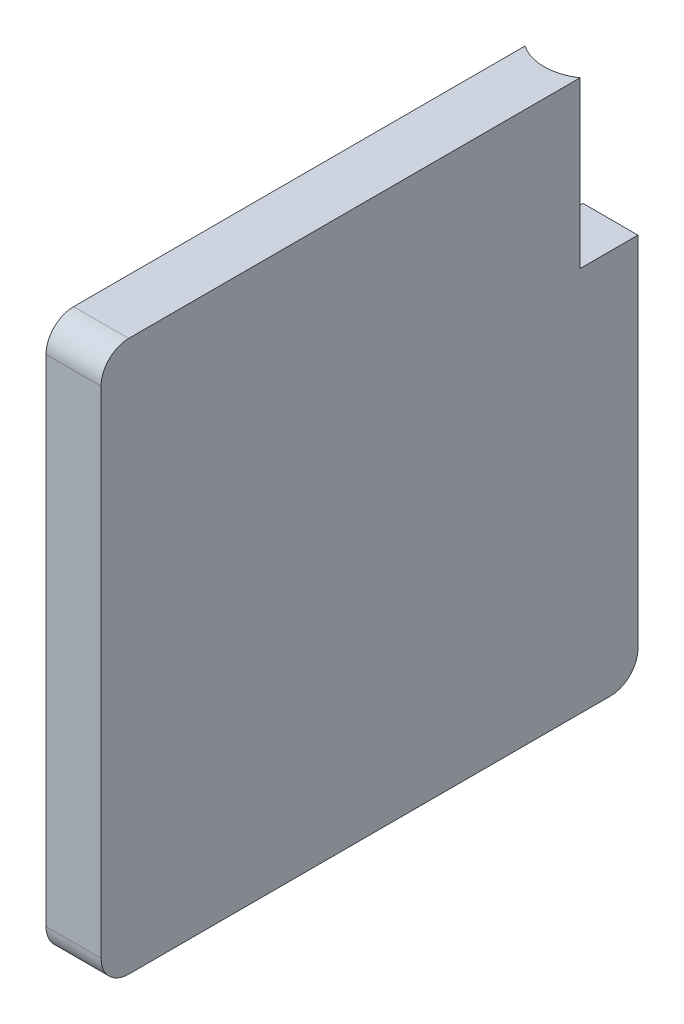
SolidWorks part; units mm, degrees
ref_plane "Front Plane" through (0, 0, 0) normal (0, 0, 1) x (1, 0, 0)
ref_plane "Top Plane" through (0, 0, 0) normal (0, 1, 0) x (1, 0, 0)
ref_plane "Right Plane" through (0, 0, 0) normal (1, 0, 0) x (0, 0, -1)
sketch "Sketch1" plane through (0, 0, 0) normal (0, 0, 1) x (1, 0, 0)
  line L1 (-4, 25.4908) -> (0, 25.4908)
  line L2 (-4, 25.4908) -> (-4, -14.5092)
  line L3 (-4, -14.5092) -> (0, -14.5092)
  line L4 (0, 25.4908) -> (0, -14.5092)
  dimension "D1" = 40
  dimension "D2" = 4
extrude "Boss-Extrude1" add sketch "Sketch1" along normal blind 39
ref_plane "Plane1" through (0, 0, 0) normal (1, 0, 0) x (0, 0, -1)
sketch "Sketch2" plane through (0, 0, 0) normal (1, 0, 0) x (0, 0, -1)
  line L1 (0, 25.4908) -> (-4, 25.4908)
  line L2 (0, 25.4908) -> (0, 13.4908)
  line L3 (0, 13.4908) -> (-4, 13.4908)
  line L4 (-4, 25.4908) -> (-4, 13.4908)
  dimension "D1" = 12
  dimension "D2" = 4
extrude "Cut-Extrude1" cut sketch "Sketch2" against normal blind 39
sketch "Sketch5" plane through (0, 25.4908, 0) normal (0, 1, 0) x (1, 0, 0)
  circle A0 centre (-2, -1.2499) radius 3.5679
extrude "Cut-Extrude3" cut sketch "Sketch5" against normal blind 12
fillet "Fillet6" radius 2 1 edges at (-2, 25.4908, 39)
fillet "Fillet7" radius 2 2 edges at (-2, -14.5092, 0) (-2, -14.5092, 39)
